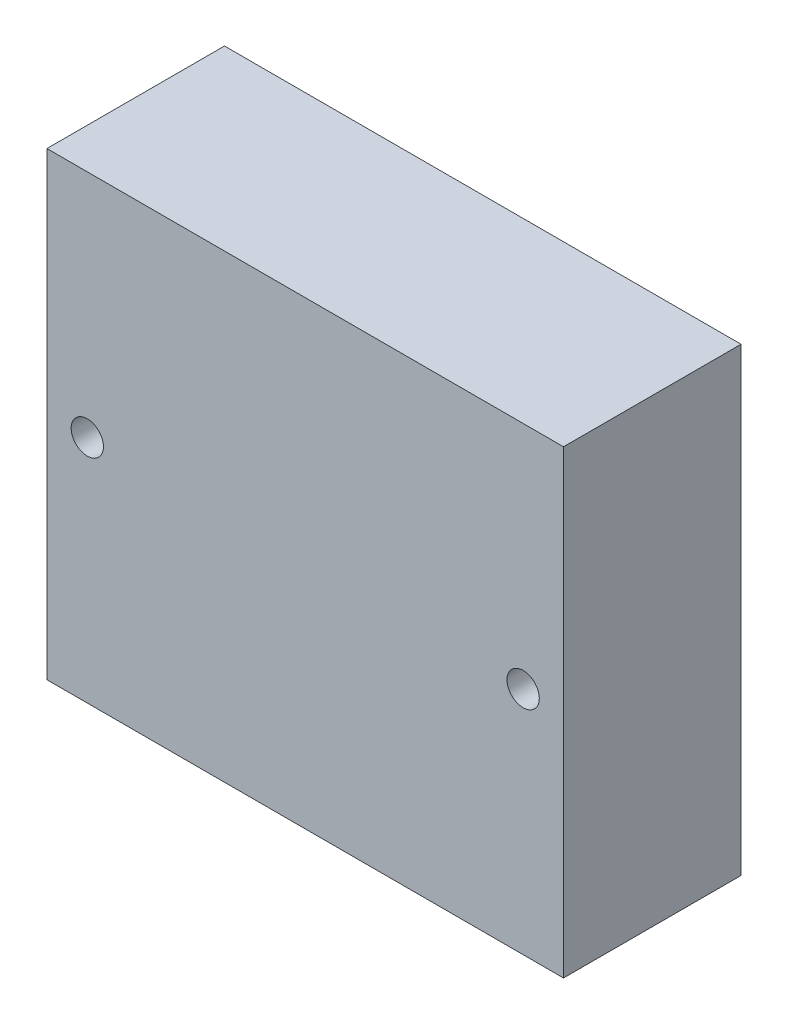
SolidWorks part; units mm, degrees
ref_plane "Plan de face" through (0, 0, 0) normal (0, 0, 1) x (1, 0, 0)
ref_plane "Plan de dessus" through (0, 0, 0) normal (0, 1, 0) x (1, 0, 0)
ref_plane "Plan de droite" through (0, 0, 0) normal (1, 0, 0) x (0, 0, -1)
sketch "Esquisse1" plane through (0, 0, 0) normal (0, 0, 1) x (1, 0, 0)
  line L1 (-32, -28.5) -> (32, -28.5)
  line L2 (-32, -28.5) -> (-32, 28.5)
  line L3 (-32, 28.5) -> (32, 28.5)
  line L4 (32, -28.5) -> (32, 28.5)
  line L5 (-32, -28.5) -> (32, 28.5) construction
  line L6 (-32, 28.5) -> (32, -28.5) construction
  circle A0 centre (-27, 0) radius 2
  circle A1 centre (27, 0) radius 2
  point P0 (0, 0)
  point P10 (32, 0)
  point P11 (0, 0)
  point P13 (24.2105, 10.6427)
  dimension "D5" = 4
  dimension "D1" = 64
  dimension "D2" = 57
  dimension "D3" = 5
  dimension "D4" = 5
extrude "Boss.-Extru.1" add sketch "Esquisse1" along normal blind 22
